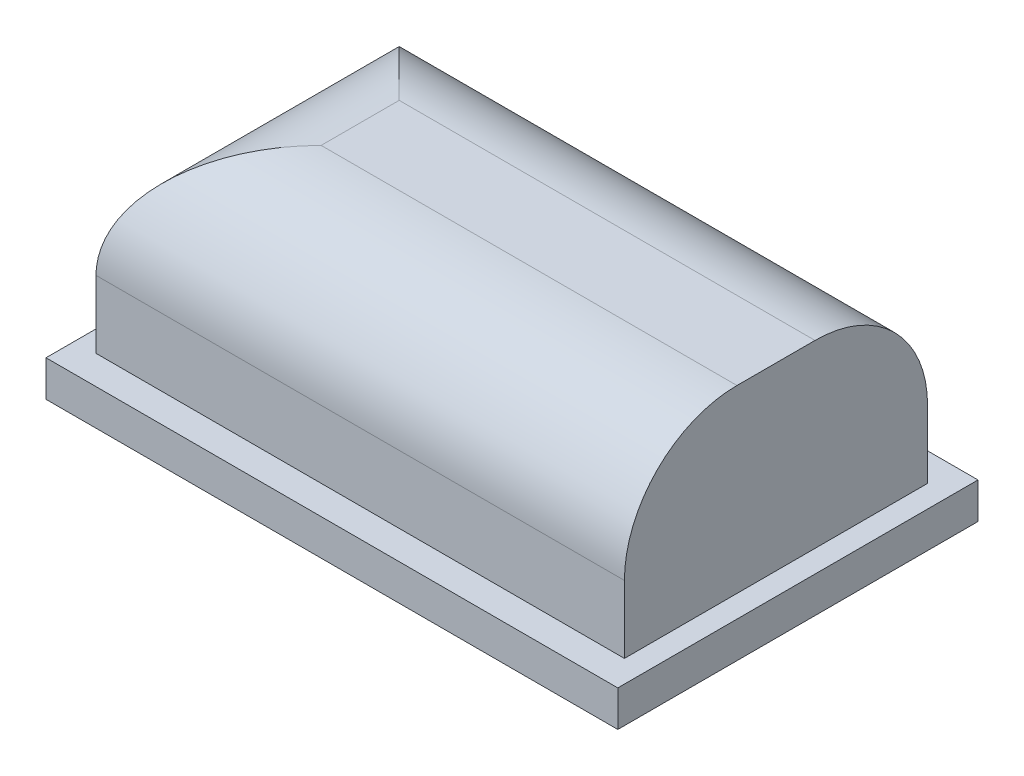
SolidWorks part; units mm, degrees
ref_plane "Front Plane" through (0, 0, 0) normal (0, 0, 1) x (1, 0, 0)
ref_plane "Top Plane" through (0, 0, 0) normal (0, 1, 0) x (1, 0, 0)
ref_plane "Right Plane" through (0, 0, 0) normal (1, 0, 0) x (0, 0, -1)
sketch "Sketch1" plane through (0, 0, 0) normal (0, 1, 0) x (1, 0, 0)
  line L1 (0, 0) -> (25.4, 0)
  line L2 (0, 0) -> (0, 16)
  line L3 (0, 16) -> (25.4, 16)
  line L4 (25.4, 0) -> (25.4, 16)
  dimension "D1" = 25.4
  dimension "D2" = 16
extrude "Boss-Extrude1" add sketch "Sketch1" along normal blind 1.6
sketch "Sketch2" plane through (0, 1.6, 0) normal (0, 1, 0) x (1, 0, 0)
  line L1 (0.9419, 1.2803) -> (24.4134, 1.2803)
  line L2 (0.9419, 1.2803) -> (0.9419, 14.747)
  line L3 (0.9419, 14.747) -> (24.4134, 14.747)
  line L4 (24.4134, 1.2803) -> (24.4134, 14.747)
extrude "Boss-Extrude2" add sketch "Sketch2" along normal blind 8
fillet "Fillet1" radius 5 3 edges at (12.6776, 9.6, -14.747) (12.6776, 9.6, -1.2803) (0.9419, 9.6, -8.0136)
